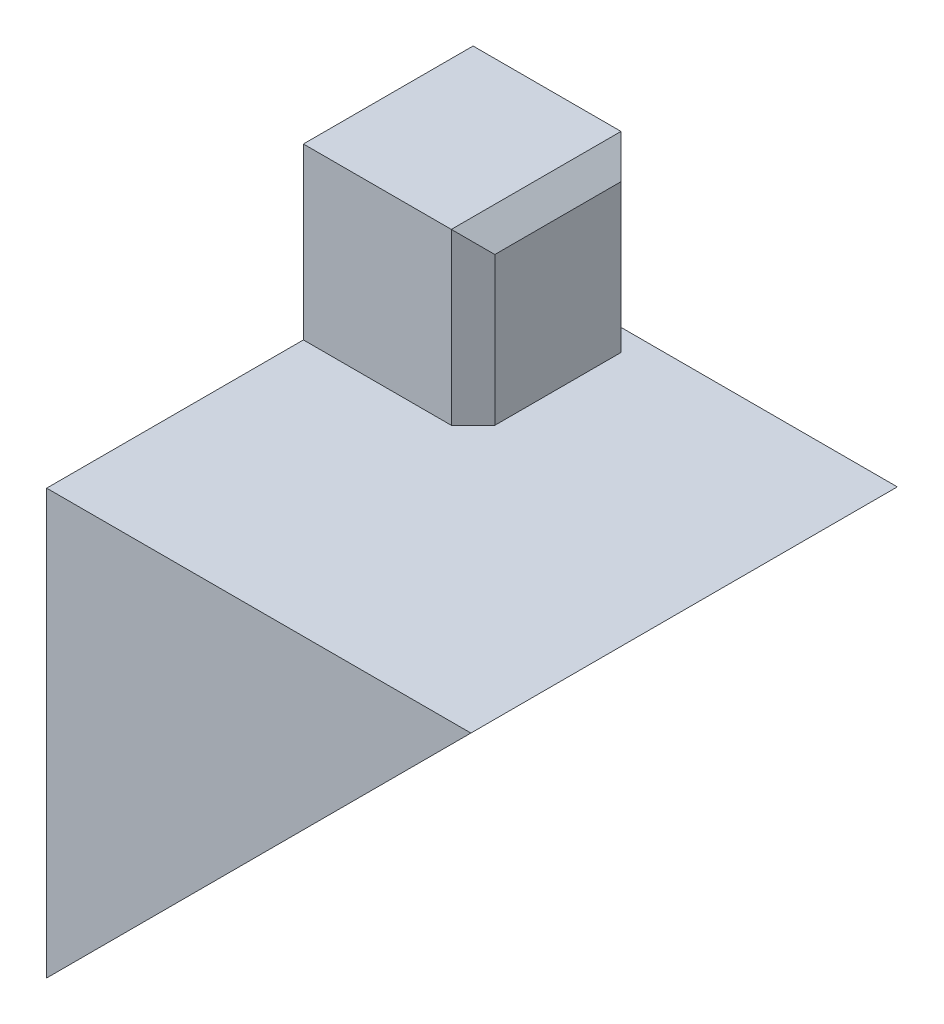
SolidWorks part; units mm, degrees
ref_plane "Front Plane" through (0, 0, 0) normal (0, 0, 1) x (1, 0, 0)
ref_plane "Top Plane" through (0, 0, 0) normal (0, 1, 0) x (1, 0, 0)
ref_plane "Right Plane" through (0, 0, 0) normal (1, 0, 0) x (0, 0, -1)
sketch "Sketch1" plane through (0, 0, 0) normal (0, 0, 1) x (1, 0, 0)
  line L0 (0, 0) -> (0, -19.5)
  line L1 (0, 0) -> (19.5, 0)
  line L2 (19.5, 0) -> (0, -19.5)
extrude "Boss-Extrude1" add sketch "Sketch1" against normal blind 19.6
sketch "Sketch2" plane through (0, 0, 0) normal (0, 1, 0) x (1, 0, 0)
  line L0 (0, 19.6) -> (19.5, 19.6)
  line L1 (19.5, 19.6) -> (19.5, 0)
  line L2 (19.5, 0) -> (0, 0)
  line L3 (0, 0) -> (0, 19.6)
  line L4 (0, 19.6) -> (0, 11.8)
  line L10 (0, 11.8) -> (7.8, 11.8)
  line L11 (7.8, 11.8) -> (7.8, 19.6)
  line L14 (0, 5.9) -> (0, 13.7)
  point P10 (9.75, 9.8)
  line M12 (0, 19.6) -> (0, 0)
extrude "Boss-Extrude4" add sketch "Sketch2" along normal blind 7.8 contours L10 L11 L0 L4 M12
chamfer "Chamfer3" distance 1 angle 45 3 edges at (7.8, 3.9, -11.8) (7.8, 7.8, -15.7) (7.8, 3.9, -19.6)
